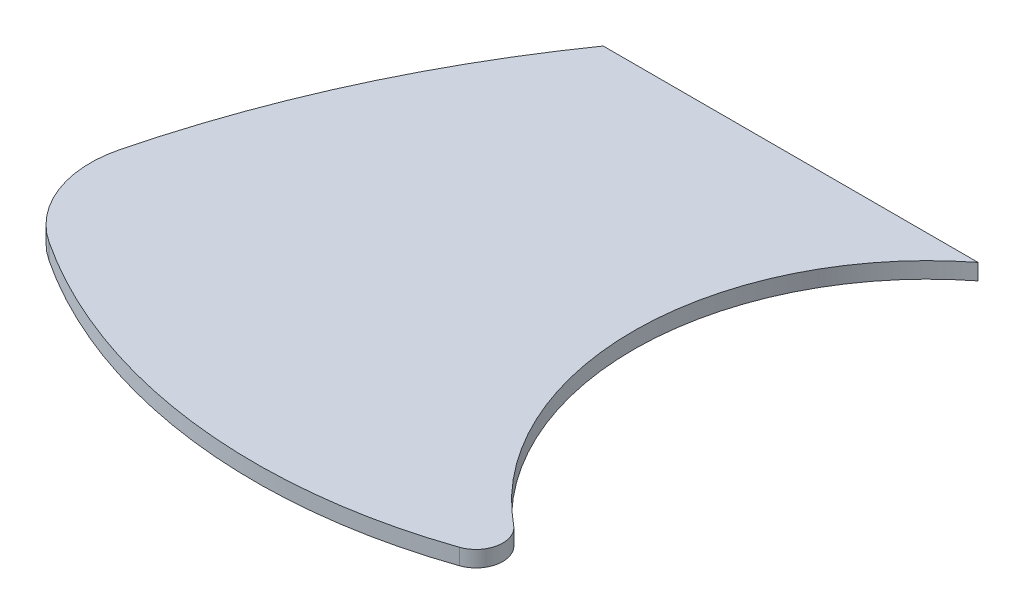
SolidWorks part; units mm, degrees
material "1023 Carbon Steel Sheet (SS)"
ref_plane "Front Plane" through (0, 0, 0) normal (1, 0, 0) x (0, 1, 0)
ref_plane "Top Plane" through (0, 0, 0) normal (0, 0, 1) x (0, 1, 0)
ref_plane "Right Plane" through (0, 0, 0) normal (0, 1, 0) x (-1, 0, 0)
sketch "Sketch2" plane through (0, 0, 0) normal (0, 1, 0) x (-1, 0, 0)
  line L0 (0, 0) -> (70, 0)
  arc A0 (90.0039, 83.5139) -> (2.3472, 94.5188) centre (35, 0) ccw
  arc A1 (0, 0) -> (0.8207, 85.9173) centre (-33.9303, 43.2867) ccw
  arc A2 (70, 0) -> (98.39, 61.8968) centre (-84.1791, 108.1759) ccw
  arc A3 (0.8207, 85.9173) -> (2.3472, 94.5188) centre (3.9799, 89.7928) cw
  arc A4 (98.39, 61.8968) -> (90.0039, 83.5139) centre (79.0031, 66.8111) ccw
  dimension "D2" = 200
  dimension "D3" = 5
  dimension "D4" = 20
  dimension "D5" = 55
  dimension "D1" = 70
extrude "Boss-Extrude1" add sketch "Sketch2" along normal blind 3
